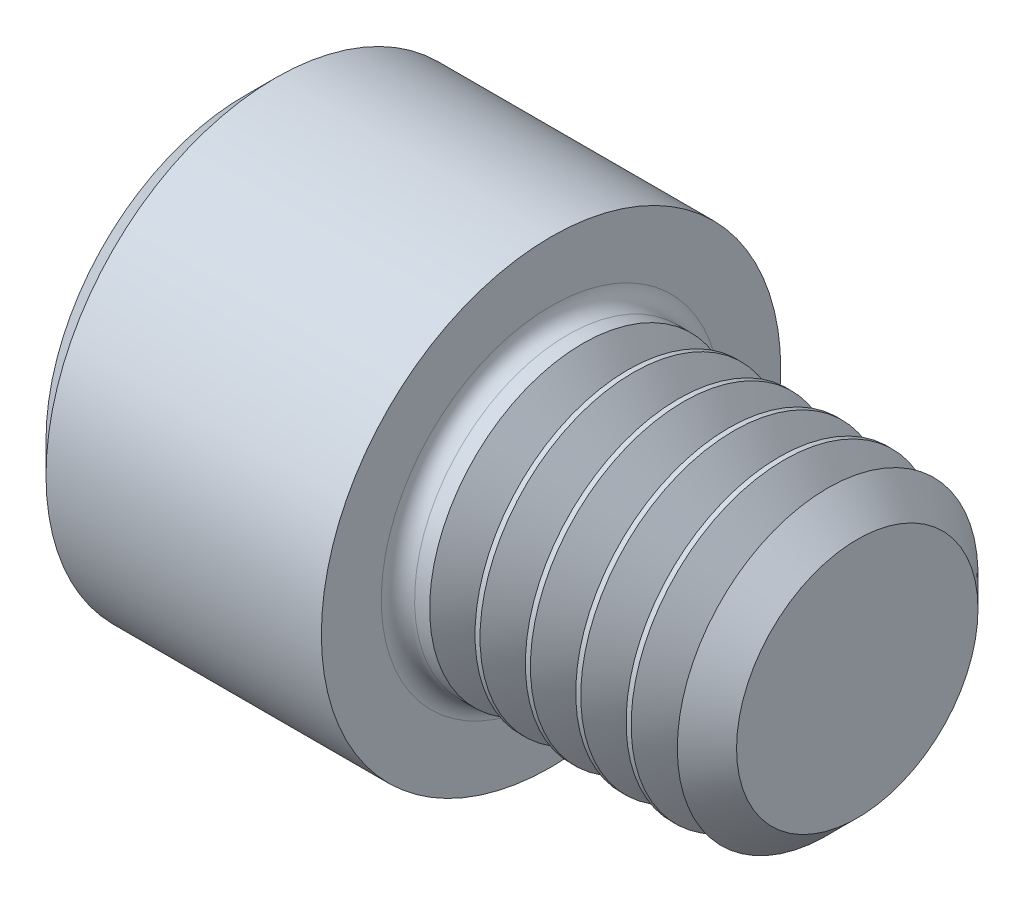
SolidWorks part; units mm, degrees
revolve "Base-Revolve" add sketch "BodySke"
sketch "BodySke" plane through (0, 0, 0) normal (0, 0, 1) x (1, 0, 0)
  line L0 (0, 0) -> (0, 5.1537)
  line L1 (0.8001, 5.9538) -> (7.9375, 5.9538)
  line L2 (7.9375, 5.9538) -> (7.9375, 3.9688)
  line L3 (7.9375, 3.9688) -> (15.0355, 3.9687)
  line L4 (15.875, 3.1293) -> (15.875, 0)
  line L5 (15.875, 0) -> (0, 0)
  line L6 (-31.75, 0) -> (127, 0) construction
  line L7 (0, 5.1537) -> (0.8001, 5.9538)
  line L8 (15.875, 3.1293) -> (15.0355, 3.9687)
  line L9 (0, -5.1537) -> (0.8001, -5.9538) construction
  line L10 (15.875, -3.1293) -> (15.0355, -3.9688) construction
  line L11 (9.3472, 9.525) -> (9.3472, 3.175) construction
  line L12 (7.9375, 9.525) -> (7.9375, 3.175) construction
  line L13 (-22.225, 9.525) -> (-22.225, 3.175) construction
  dimension "Diameter" = 7.9375
  dimension "Head_ht" = 7.9375
  dimension "Length" = 7.9375
  dimension "Body_ch_ang" = 45
  dimension "Head_dia" = 11.9075
  dimension "Head_ch_ang" = 45
  dimension "Head_side_ht" = 7.1374
  dimension "Minor_dia" = 6.2586
  dimension "Advance" = 1.4097
  dimension "Thread_nom" = 7.9375
  dimension "Thread_length" = 38.1
cosmetic thread "ThreadCosmetic" [suppressed]
fillet "Fillet1" radius 0.4318 1 edges at (7.9375, 0, 3.9688)
ref_plane "Plane1" through (0, 0, 0) normal (0, 0, 1) x (1, 0, 0)
ref_plane "Plane2" through (0, 0, 0) normal (0, 1, 0) x (1, 0, 0)
ref_plane "Plane3" through (0, 0, 0) normal (1, 0, 0) x (0, 0, -1)
other "Configuration Table"
sketch "Sketch2" plane through (0, 0, 0) normal (0, 0, 1) x (1, 0, 0)
  line L0 (0, 3.175) -> (3.8354, 3.175)
  line L1 (3.8354, 3.175) -> (5.6685, 0)
  line L2 (-31.75, 0) -> (127, 0) construction
  line L3 (5.6685, 0) -> (0, 0)
  line L4 (0, 0) -> (0, 3.175)
  line L5 (0, 5.1537) -> (0, -5.1537) construction
  line L6 (0, 0) -> (47.625, 0) construction
  line L7 (7.9375, -5.9538) -> (7.9375, 5.9538) construction
  dimension "D1" = 3.175
  dimension "D2" = 60
revolve "Hex-PreBroach" cut sketch "Sketch2" angle 360 about L6
sketch "Sketch3" plane through (0, 0, 0) normal (-1, 0, 0) x (0, 0.5, 0.866)
  line L0 (1.8331, 3.175) -> (-1.8331, 3.175)
  line L1 (-1.8331, 3.175) -> (-3.6662, 0)
  line L2 (1.8331, 3.175) -> (3.6662, 0)
  line L3 (1.8331, -3.175) -> (3.6662, 0)
  line L4 (1.8331, -3.175) -> (-1.8331, -3.175)
  line L5 (-1.8331, -3.175) -> (-3.6662, 0)
  dimension "D1" = 3.175
  dimension "D2" = 3.175
  dimension "Hex_size" = 6.35
extrude "Hex" cut sketch "Sketch3" against normal blind 3.8354
sketch "Sketch4" plane through (0, 0, 0) normal (-1, 0, 0) x (0, 0, 1)
  line L0 (0, 0) -> (3.7846, 0)
  line L1 (0, 0) -> (6.1484, 3.5498) construction
  line L2 (0, 0) -> (1.8923, 3.2776)
  line L3 (3.1235, 0.8061) -> (3.6229, 1.0945)
  line L4 (2.2599, 2.3019) -> (2.7593, 2.5903)
  arc A0 (3.1235, 0.8061) -> (2.2599, 2.3019) centre (0, 0) ccw
  arc A1 (3.7846, 0) -> (3.6229, 1.0945) centre (0, 0) ccw
  arc A2 (1.8923, 3.2776) -> (2.7593, 2.5903) centre (0, 0) cw
  dimension "D1" = 30
  dimension "D2" = 60
  dimension "Spline_p_dim" = 1.7272
  dimension "D3" = 0.8636
extrude "Spline" [suppressed] cut sketch "Sketch4" against normal blind 3.8354
pattern_circular "CirPattern1" [suppressed] count 6 every 60
sketch "Sketch5" plane through (0, 0, 0) normal (0, 0, 1) x (1, 0, 0)
  line L0 (-31.75, 0) -> (127, 0) construction
  line L2 (0, 5.1537) -> (0, -5.1537) construction
  circle A0 centre (2.6416, 0) radius 0.5905
  dimension "Drilled_hole_dia" = 1.1811
  dimension "Drilled_hole_loc" = 2.6416
extrude "Hole" [suppressed] cut sketch "Sketch5" against normal through all and the other way through all
pattern_circular "Drilled-4" [suppressed] count 2 every 60
pattern_circular "Drilled-6" [suppressed] count 3 every 60
sketch "ThdSchSke" plane through (0, 0, 0) normal (0, 0, 1) x (1, 0, 0)
  line L0 (9.3472, -3.1293) -> (8.7594, -3.9688)
  line L1 (9.3472, -3.1293) -> (9.935, -3.9688)
  line L2 (9.935, -3.9688) -> (9.935, -4.9609)
  line L3 (-3.175, 0) -> (5.1513, 0) construction
  line L5 (9.935, -4.9609) -> (8.7594, -4.9609)
  line L6 (8.7594, -4.9609) -> (8.7594, -3.9688)
  line L7 (0, 5.1537) -> (0, -5.1537) construction
  dimension "Thread_minor" = 6.2586
  dimension "Diameter" = 7.9375
  dimension "Start" = 9.3472
revolve "ThreadSchematic" cut sketch "ThdSchSke" angle 360 about L3
pattern_linear "ThdSchPat" count 5 spacing 1.3056 along (1, 0, 0) of "ThreadSchematic"
equation "\"D2@Sketch3\" = \"Hex_size@Sketch3\" / 2"
equation "\"D1@Sketch3\" = \"Hex_size@Sketch3\" / 2"
equation "\"D1@Sketch2\" = \"Hex_size@Sketch3\" / 2"
equation "\"D3@Sketch4\" = \"Spline_p_dim@Sketch4\" / 2"
equation "\"Thread_minor@ThreadCosmetic\"  =  \"Minor_dia@BodySke\""
equation "\"D2@CirPattern1\" = 360 / \"Num_teeth@CirPattern1\""
equation "\"Wall_thickness@Sketch2\" = \"Head_ht@BodySke\" - \"Key_eng@Hex\""
equation "\"Thread_length@ThreadCosmetic\" = ((sgn( (\"Length@BodySke\" - \"Advance@BodySke\" ) - \"Thread_nom@BodySke\" )-1)*( (\"Length@BodySke\" - \"Advance@BodySke\" ) - \"Thread_nom@BodySke\" ))/-2+ \"Thread_nom@BodySke\""
equation "\"Thread_minor@ThdSchSke\" = \"Minor_dia@BodySke\""
equation "\"Diameter@ThdSchSke\" = \"Diameter@BodySke\""
equation "\"Overcut@ThdSchSke\" = \"Diameter@BodySke\" * 1.25"
equation "\"Start@ThdSchSke\" = \"Head_ht@BodySke\" + \"Length@BodySke\" - \"Thread_length@ThreadCosmetic\"  '---Non-countersunk---"
equation "\"Num_threads@ThdSchPat\" = int( \"Thread_length@ThreadCosmetic\" / \"Advance@BodySke\" + 0.999 )  + 1"
equation "\"Advance@ThdSchPat\" = \"Thread_length@ThreadCosmetic\" /  (\"Num_threads@ThdSchPat\" - 1) 'relax it"
equation "\"Num_threads@ThdSchPat\" = \"Num_threads@ThdSchPat\" - sgn( \"Num_threads@ThdSchPat\" - 1) '---chamfered tips only---"
